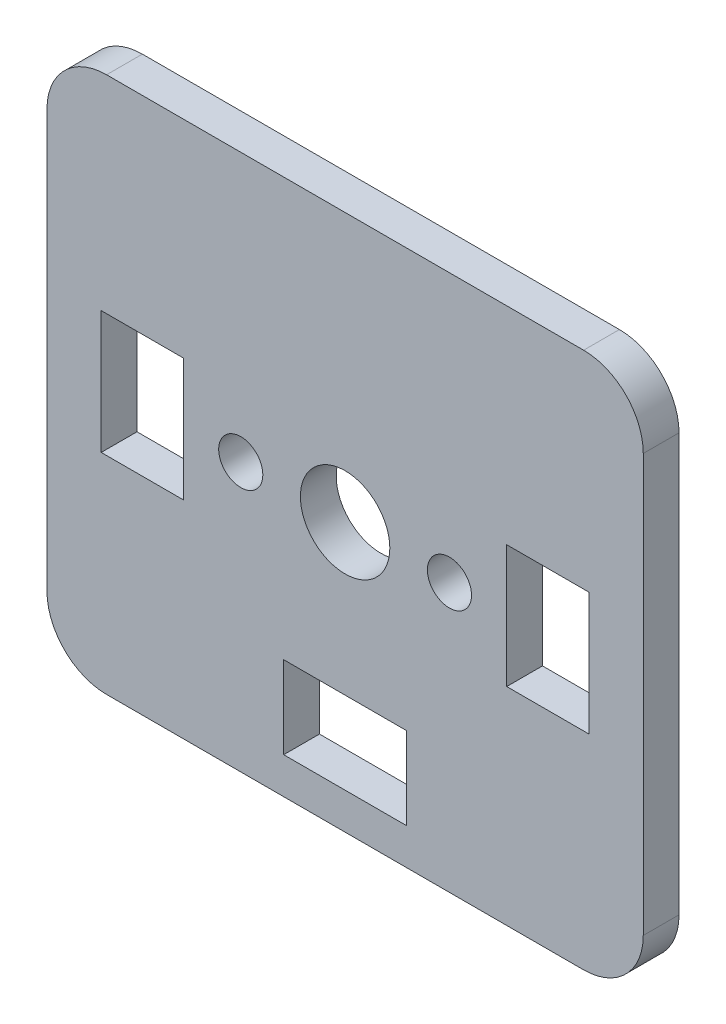
SolidWorks part; units mm, degrees
ref_plane "Front Plane" through (0, 0, 0) normal (0, 0, 1) x (1, 0, 0)
ref_plane "Top Plane" through (0, 0, 0) normal (0, 1, 0) x (1, 0, 0)
ref_plane "Right Plane" through (0, 0, 0) normal (1, 0, 0) x (0, 0, -1)
sketch "Sketch1" plane through (0, 0, 0) normal (0, 0, 1) x (1, 0, 0)
  line L0 (0, 16.9365) -> (0, -25.309) construction
  line L1 (-25, -22.5) -> (25, -22.5)
  line L2 (-25, -22.5) -> (-25, 22.5)
  line L3 (-25, 22.5) -> (25, 22.5)
  line L4 (25, -22.5) -> (25, 22.5)
  line L5 (-25, -22.5) -> (25, 22.5) construction
  line L6 (-25, 22.5) -> (25, -22.5) construction
  line L7 (-25, 0) -> (16.286, 0) construction
  line L8 (20.45, -5.15) -> (13.55, -5.15)
  line L13 (13.55, 5.15) -> (13.55, -5.15)
  line L14 (20.45, 5.15) -> (13.55, 5.15)
  line L15 (-20.45, 5.15) -> (-13.55, 5.15)
  line L16 (-20.45, 5.15) -> (-20.45, -5.15)
  line L17 (-20.45, -5.15) -> (-13.55, -5.15)
  line L18 (-13.55, 5.15) -> (-13.55, -5.15)
  line L19 (-20.45, 5.15) -> (-13.55, -5.15) construction
  line L20 (-20.45, -5.15) -> (-13.55, 5.15) construction
  line L21 (-5.15, -12.55) -> (5.15, -12.55)
  line L22 (-5.15, -12.55) -> (-5.15, -19.45)
  line L23 (-5.15, -19.45) -> (5.15, -19.45)
  line L24 (5.15, -12.55) -> (5.15, -19.45)
  line L25 (-5.15, -12.55) -> (5.15, -19.45) construction
  line L26 (-5.15, -19.45) -> (5.15, -12.55) construction
  line L27 (20.45, 5.15) -> (20.45, -5.15)
  circle A0 centre (0, 0) radius 3.75
  circle A1 centre (8.75, 0) radius 1.85
  circle A2 centre (-8.75, 0) radius 1.85
  point P0 (0, 0)
  point P16 (0, 0)
  point P17 (-17, 0)
  point P20 (0, 16)
  point P27 (0, -16)
  dimension "D3" = 3.7
  dimension "D4" = 7.5
  dimension "D1" = 45
  dimension "D2" = 50
  dimension "D5" = 8.75
  dimension "D6" = 6.9
  dimension "D8" = 16
  dimension "D9" = 8
  dimension "D10" = 10.3
extrude "Boss-Extrude1" add sketch "Sketch1" along normal blind 3
fillet "Fillet1" radius 5 4 edges at (-25, 22.5, 1.5) (-25, -22.5, 1.5) (25, -22.5, 1.5) (25, 22.5, 1.5)
sketch "Sketch2" plane through (0, 0, 0) normal (0, 0, -1) x (-1, 0, 0)
  line L0 (20.45, 5.15) -> (20.45, -5.15) construction
  line L1 (20.45, -5.15) -> (13.55, -5.15) construction
  line L2 (13.55, -5.15) -> (13.55, 5.15) construction
  line L3 (13.55, 5.15) -> (20.45, 5.15) construction
  line L4 (5.15, -12.55) -> (5.15, -19.45) construction
  line L5 (5.15, -19.45) -> (-5.15, -19.45) construction
  line L6 (-5.15, -19.45) -> (-5.15, -12.55) construction
  line L7 (-5.15, -12.55) -> (5.15, -12.55) construction
  line L8 (-13.55, 5.15) -> (-13.55, -5.15) construction
  line L9 (-20.45, -5.15) -> (-20.45, 5.15) construction
  line L10 (-13.55, -5.15) -> (-20.45, -5.15) construction
  line L11 (-20.45, 5.15) -> (-13.55, 5.15) construction
  line L12 (20.45, 5.15) -> (20.45, -5.15)
  line L13 (20.45, -5.15) -> (13.55, -5.15)
  line L14 (13.55, -5.15) -> (13.55, 5.15)
  line L15 (13.55, 5.15) -> (20.45, 5.15)
  line L16 (5.15, -12.55) -> (5.15, -19.45)
  line L17 (5.15, -19.45) -> (-5.15, -19.45)
  line L18 (-5.15, -19.45) -> (-5.15, -12.55)
  line L19 (-5.15, -12.55) -> (5.15, -12.55)
  line L20 (-13.55, 5.15) -> (-13.55, -5.15)
  line L21 (-20.45, -5.15) -> (-20.45, 5.15)
  line L22 (-13.55, -5.15) -> (-20.45, -5.15)
  line L23 (-20.45, 5.15) -> (-13.55, 5.15)
